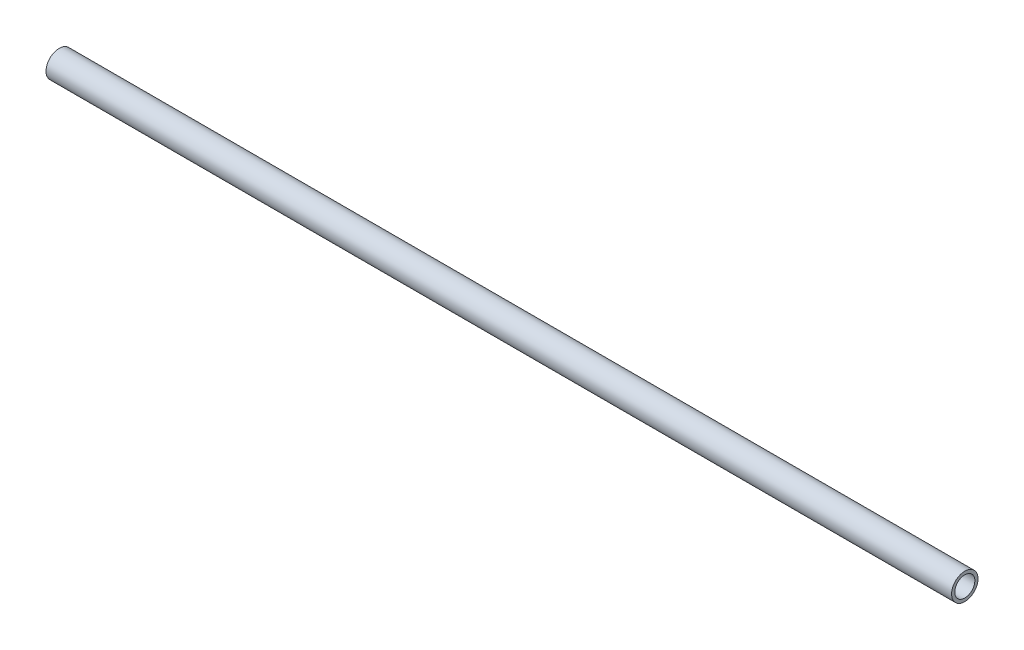
SolidWorks part; units mm, degrees
material "AISI 4130 Steel, annealed at 865C"
ref_plane "Front Plane" through (0, 0, 0) normal (0, 0, 1) x (1, 0, 0)
ref_plane "Top Plane" through (0, 0, 0) normal (0, 1, 0) x (1, 0, 0)
ref_plane "Right Plane" through (0, 0, 0) normal (1, 0, 0) x (0, 0, -1)
sketch "Sketch1" plane through (0, 0, 0) normal (1, 0, 0) x (0, 0, -1)
  circle A0 centre (0, 0) radius 12.7
  circle A1 centre (0, 0) radius 9.652
  dimension "D1" = 25.4
  dimension "D2" = 19.304
extrude "Boss-Extrude1" add sketch "Sketch1" along normal blind 870
